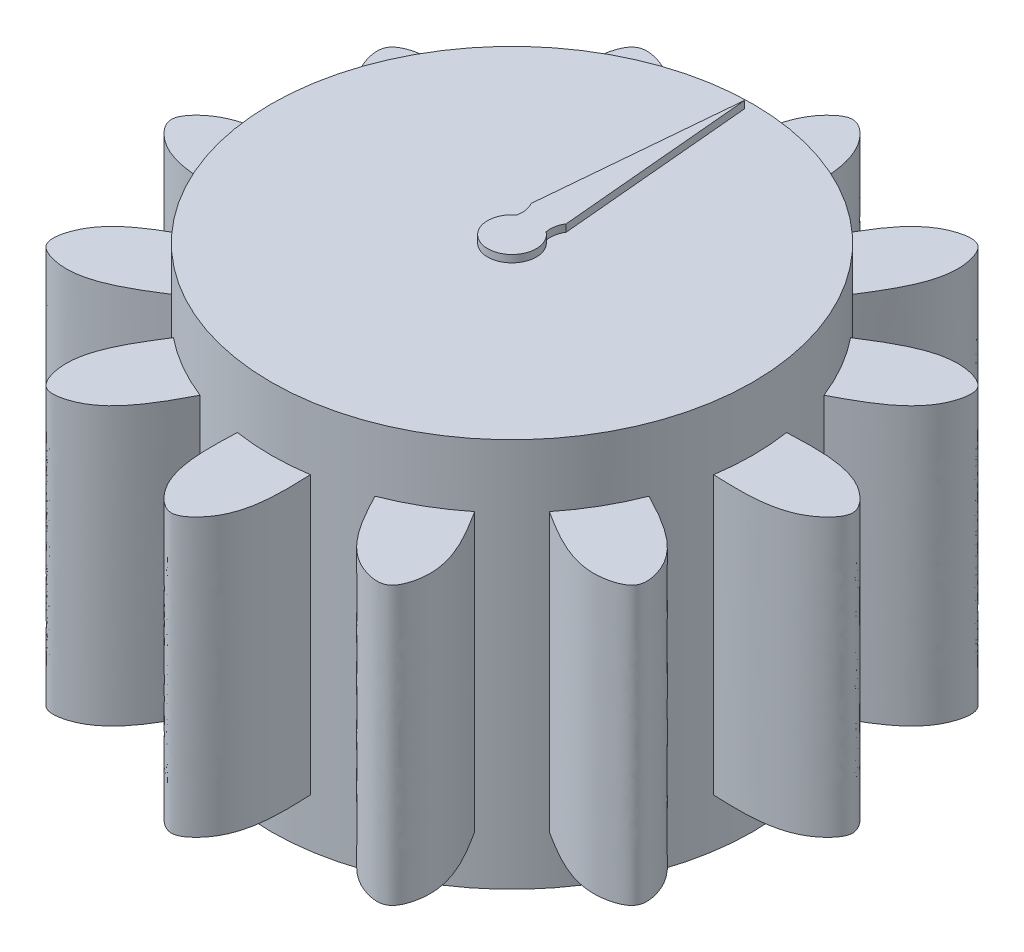
SolidWorks part; units mm, degrees
ref_plane "Front Plane" through (0, 0, 0) normal (0, 0, 1) x (1, 0, 0)
ref_plane "Top Plane" through (0, 0, 0) normal (0, 1, 0) x (1, 0, 0)
ref_plane "Right Plane" through (0, 0, 0) normal (1, 0, 0) x (0, 0, -1)
sketch "Sketch1" plane through (0, 0, 0) normal (0, 1, 0) x (1, 0, 0)
  line L0 (0, 0) -> (0, 10) construction
  circle A12 centre (0, 0) radius 9.9
  point P43 (0, 0)
  dimension "D1" = 19.8
extrude "Boss-Extrude1" add sketch "Sketch1" along normal blind 12
sketch "Sketch4" plane through (0, 0, 0) normal (0, -1, 0) x (1, 0, 0)
  line L0 (-1.5, -9.7857) -> (1.5, -9.7857)
  circle A1 centre (0, 0) radius 9.9 construction
  spline S0 degree 3 poles (1.5, -9.7857) (1.5223, -10.3509) (1.5744, -11.6677) (1.1993, -13.2812) (0, -14.189) (-1.1993, -13.2812) (-1.5744, -11.6677) (-1.5223, -10.3509) (-1.5, -9.7857) knots 0 0 0 0 0.178316 0.415433 0.5 0.584567 0.821684 1 1 1 1
  dimension "D1" = 3
  dimension "D2" = 3
  dimension "D3" = 14
  dimension "D4" = 1.4
  dimension "D5" = 0.4
  dimension "D6" = 0.7
  dimension "D7" = 1.7
  dimension "D8" = 4.2143
sketch "Sketch2" plane through (0, 12, 0) normal (0, 1, 0) x (1, 0, 0)
  circle A0 centre (0, 0) radius 9.9
  dimension "D1" = 19.8
extrude "Boss-Extrude2" add sketch "Sketch2" along normal blind 2
sketch "Sketch3" plane through (0, 14, 0) normal (0, 1, 0) x (1, 0, 0)
  line L0 (0, 0) -> (0, 1) construction
  line L2 (0, 1) -> (0, 9.5619) construction
  line L3 (0, 9.5619) -> (0.7279, 1.5)
  line L4 (0, 9.5619) -> (-0.7174, 1.5002)
  arc A0 (-0.6, 0.8) -> (0.6, 0.8) centre (0, 0) ccw
  arc A1 (0.7279, 1.5) -> (0.6, 0.8) centre (1.5527, 0.9877) ccw
  arc A2 (-0.7174, 1.5002) -> (-0.6, 0.8) centre (-1.55, 1.0007) cw
  point P6 (0.7279, 1.5)
  dimension "D1" = 2
  dimension "D3" = 0.971
  dimension "D6" = 8.5619
  dimension "D2" = 1.2
  dimension "D4" = 0.7116
  dimension "D5" = 0.71
  dimension "D7" = 0.9527
  dimension "D8" = 0.95
  dimension "D9" = 1.8402
extrude "Boss-Extrude3" add sketch "Sketch3" along normal blind 0.3 contours A1 A0 A2 L4 L3
extrude "Boss-Extrude5" add sketch "Sketch4" against normal blind 11.4
pattern_circular "CirPattern1" count 12 over 360 about axis through (0, 0, 0) along (0, 1, 0) of "Boss-Extrude5"
sketch "Sketch5" plane through (0, 0, 0) normal (0, -1, 0) x (1, 0, 0)
  circle A0 centre (0, 0) radius 9.9
  dimension "D1" = 19.8
extrude "Boss-Extrude6" add sketch "Sketch5" along normal blind 2
sketch "Sketch6" plane through (0, -2, 0) normal (0, -1, 0) x (1, 0, 0)
  line L0 (0, -9.5619) -> (0.7279, -1.5) construction
  line L1 (0, -9.5619) -> (-0.7174, -1.5002) construction
  line L2 (0, -9.5619) -> (0.7279, -1.5)
  line L3 (0, -9.5619) -> (-0.7174, -1.5002)
  arc A0 (0.6, -0.8) -> (0.7279, -1.5) centre (1.5527, -0.9877) ccw construction
  arc A1 (0.6, -0.8) -> (-0.6, -0.8) centre (0, 0) ccw construction
  arc A2 (-0.7174, -1.5002) -> (-0.6, -0.8) centre (-1.55, -1.0007) ccw construction
  arc A3 (0.6, -0.8) -> (0.7279, -1.5) centre (1.5527, -0.9877) ccw
  arc A4 (0.6, -0.8) -> (-0.6, -0.8) centre (0, 0) ccw
  arc A5 (-0.7174, -1.5002) -> (-0.6, -0.8) centre (-1.55, -1.0007) ccw
extrude "Boss-Extrude7" add sketch "Sketch6" along normal blind 0.3
